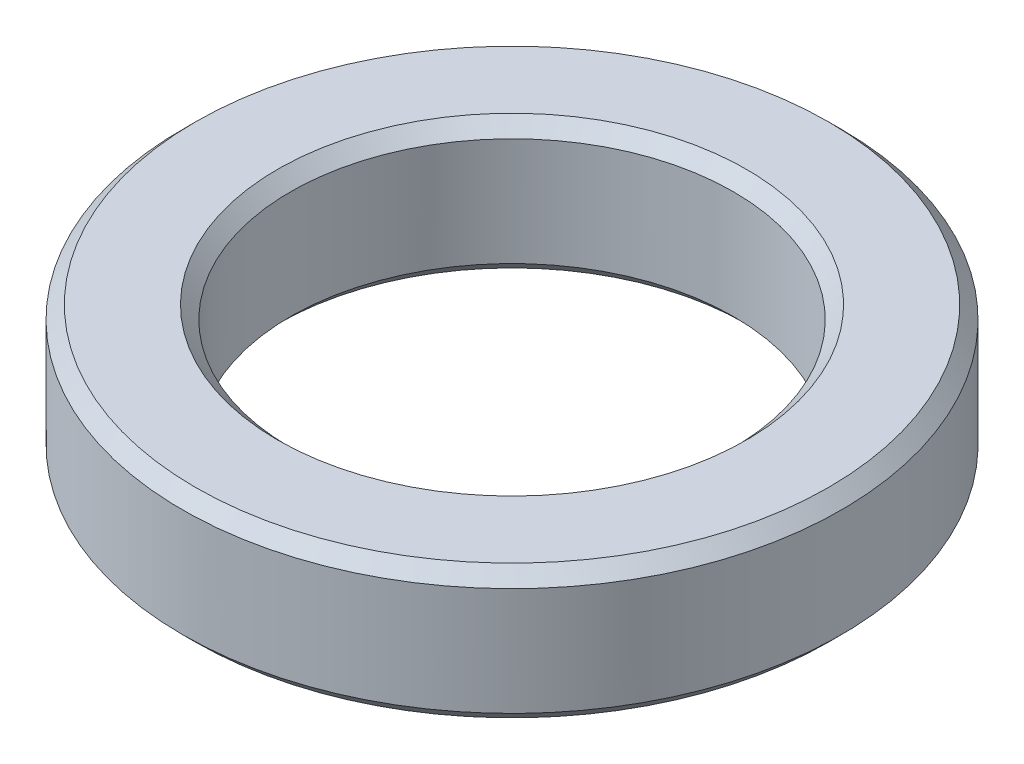
SolidWorks part; units mm, degrees
ref_plane "Front Plane" through (0, 0, 0) normal (0, 0, 1) x (1, 0, 0)
ref_plane "Top Plane" through (0, 0, 0) normal (0, 1, 0) x (1, 0, 0)
ref_plane "Right Plane" through (0, 0, 0) normal (1, 0, 0) x (0, 0, -1)
sketch "Sketch1" plane through (0, 0, 0) normal (0, 1, 0) x (1, 0, 0)
  circle A0 centre (0, 0) radius 10.25
  circle A1 centre (0, 0) radius 15.25
  dimension "D1" = 20.5
  dimension "D2" = 5
extrude "Boss-Extrude1" add sketch "Sketch1" along normal blind 6.2
chamfer "Chamfer1" distance 0.6 angle 45 4 edges at (0, 0, 10.25) (0, 0, 15.25) (0, 6.2, 10.25) (0, 6.2, 15.25)
